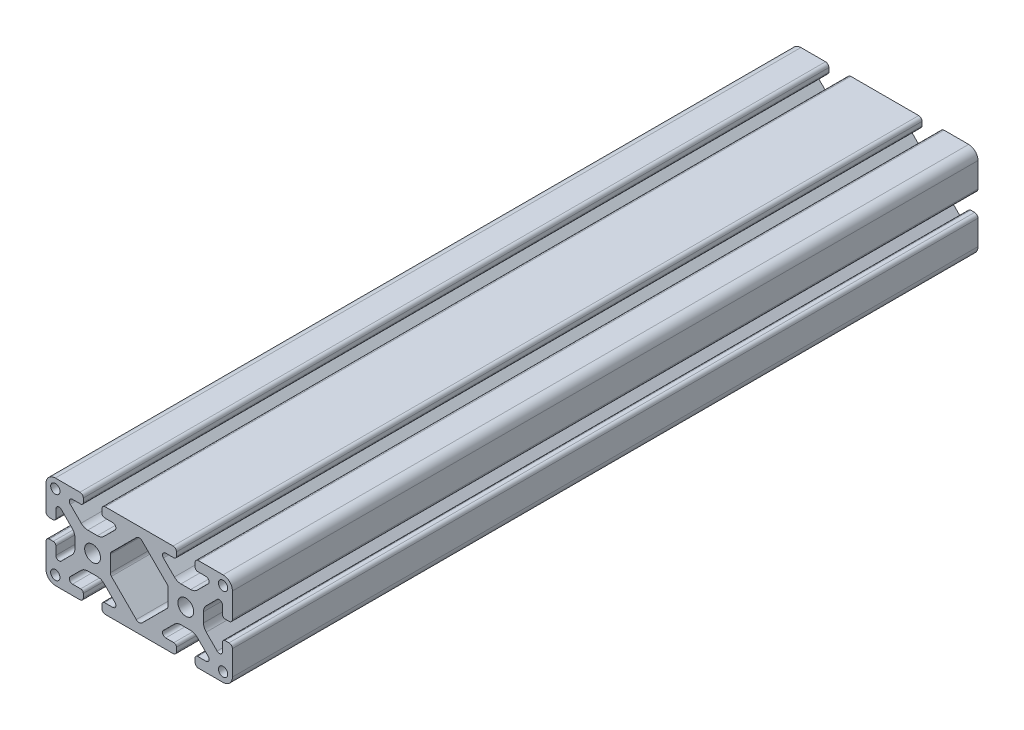
SolidWorks part; units mm, degrees
ref_plane "Front" through (0, 0, 0) normal (0, 0, 1) x (1, 0, 0)
ref_plane "Top" through (0, 0, 0) normal (0, 1, 0) x (1, 0, 0)
ref_plane "Right" through (0, 0, 0) normal (1, 0, 0) x (0, 0, -1)
sketch "Support-Front" plane through (0, 0, 0) normal (0, 0, 1) x (1, 0, 0)
  line L0 (50, 0) -> (-50, 0) construction
  line L1 (-50, -25) -> (50, -25)
  line L2 (-50, -25) -> (-50, 25)
  line L3 (-50, 25) -> (50, 25)
  line L4 (50, -25) -> (50, 25)
  line L5 (0, 25) -> (0, -25) construction
  dimension "Height-Profile" = 50
  dimension "Width-Profile" = 100
sketch "Support-Right-Length" plane through (0, 0, 0) normal (1, 0, 0) x (0, 0, -1)
  line L0 (0, -25) -> (0, 25) construction
  line L1 (-200, 25) -> (200, 25)
  line L2 (-200, 25) -> (-200, -25)
  line L3 (-200, -25) -> (200, -25)
  line L4 (200, 25) -> (200, -25)
  dimension "Length-Profile" = 400
sketch "Support-Profile" plane through (0, 0, 0) normal (0, 0, 1) x (1, 0, 0)
  line L12 (-14.9142, -5.6858) -> (-1.5556, -19.0444)
  line L13 (-15.5, 4.2716) -> (-15.5, -4.2716)
  line L14 (-1.5556, 19.0444) -> (-14.9142, 5.6858)
  line L15 (14.9142, 5.6858) -> (1.5556, 19.0444)
  line L16 (15.5, -4.2716) -> (15.5, 4.2716)
  line L17 (1.5556, -19.0444) -> (14.9142, -5.6858)
  line L104 (-30, -23.2) -> (-30, -21.1)
  line L105 (-31.4, -19.7) -> (-35.8, -19.7)
  line L106 (-36.9987, -16.7945) -> (-31.1255, -10.9545)
  line L107 (-27.6, -9.5) -> (-22.4, -9.5)
  line L108 (-18.8745, -10.9545) -> (-13.0013, -16.7945)
  line L109 (-14.2, -19.7) -> (-18.6, -19.7)
  line L110 (-20, -21.1) -> (-20, -23.2)
  line L111 (-18.2, -25) -> (18.2, -25)
  line L112 (20, -23.2) -> (20, -21.1)
  line L113 (18.6, -19.7) -> (14.2, -19.7)
  line L114 (13.0013, -16.7945) -> (18.8745, -10.9545)
  line L115 (22.4, -9.5) -> (27.6, -9.5)
  line L116 (31.1255, -10.9545) -> (36.9987, -16.7945)
  line L117 (35.8, -19.7) -> (31.4, -19.7)
  line L118 (30, -21.1) -> (30, -23.2)
  line L119 (31.8, -25) -> (45, -25)
  line L120 (50, -20) -> (50, -6.8)
  line L121 (48.2, -5) -> (46.1, -5)
  line L122 (44.7, -6.4) -> (44.7, -10.8)
  line L123 (41.7945, -11.9987) -> (35.9545, -6.1255)
  line L124 (34.5, -2.6) -> (34.5, 2.6)
  line L125 (35.9545, 6.1255) -> (41.7945, 11.9987)
  line L126 (44.7, 10.8) -> (44.7, 6.4)
  line L127 (46.1, 5) -> (48.2, 5)
  line L128 (50, 6.8) -> (50, 20)
  line L129 (45, 25) -> (31.8, 25)
  line L130 (30, 23.2) -> (30, 21.1)
  line L131 (31.4, 19.7) -> (35.8, 19.7)
  line L132 (36.9987, 16.7945) -> (31.1255, 10.9545)
  line L133 (27.6, 9.5) -> (22.4, 9.5)
  line L134 (18.8745, 10.9545) -> (13.0013, 16.7945)
  line L135 (14.2, 19.7) -> (18.6, 19.7)
  line L136 (20, 21.1) -> (20, 23.2)
  line L137 (18.2, 25) -> (-18.2, 25)
  line L138 (-20, 23.2) -> (-20, 21.1)
  line L139 (-18.6, 19.7) -> (-14.2, 19.7)
  line L140 (-13.0013, 16.7945) -> (-18.8745, 10.9545)
  line L141 (-22.4, 9.5) -> (-27.6, 9.5)
  line L142 (-31.1255, 10.9545) -> (-36.9987, 16.7945)
  line L143 (-35.8, 19.7) -> (-31.4, 19.7)
  line L144 (-30, 21.1) -> (-30, 23.2)
  line L145 (-31.8, 25) -> (-45, 25)
  line L146 (-50, 20) -> (-50, 6.8)
  line L147 (-48.2, 5) -> (-46.1, 5)
  line L148 (-44.7, 6.4) -> (-44.7, 10.8)
  line L149 (-41.7945, 11.9987) -> (-35.9545, 6.1255)
  line L150 (-34.5, 2.6) -> (-34.5, -2.6)
  line L151 (-35.9545, -6.1255) -> (-41.7945, -11.9987)
  line L152 (-44.7, -10.8) -> (-44.7, -6.4)
  line L153 (-46.1, -5) -> (-48.2, -5)
  line L154 (-50, -6.8) -> (-50, -20)
  line L155 (-45, -25) -> (-31.8, -25)
  circle A1 centre (-25, 0) radius 4.25
  circle A3 centre (-45, 20) radius 2.5
  circle A5 centre (-45, -20) radius 2.5
  arc A12 (-15.5, -4.2716) -> (-14.9142, -5.6858) centre (-13.5, -4.2716) ccw
  arc A13 (-14.9142, 5.6858) -> (-15.5, 4.2716) centre (-13.5, 4.2716) ccw
  arc A14 (1.5556, 19.0444) -> (-1.5556, 19.0444) centre (0, 17.4887) ccw
  arc A15 (15.5, 4.2716) -> (14.9142, 5.6858) centre (13.5, 4.2716) ccw
  arc A16 (14.9142, -5.6858) -> (15.5, -4.2716) centre (13.5, -4.2716) ccw
  arc A17 (-1.5556, -19.0444) -> (1.5556, -19.0444) centre (0, -17.4887) ccw
  circle A19 centre (25, 0) radius 4.25
  circle A21 centre (45, -20) radius 2.5
  circle A23 centre (45, 20) radius 2.5
  arc A104 (-30, -21.1) -> (-31.4, -19.7) centre (-31.4, -21.1) ccw
  arc A105 (-36.9987, -16.7945) -> (-35.8, -19.7) centre (-35.8, -18) ccw
  arc A106 (-27.6, -9.5) -> (-31.1255, -10.9545) centre (-27.6, -14.5) ccw
  arc A107 (-18.8745, -10.9545) -> (-22.4, -9.5) centre (-22.4, -14.5) ccw
  arc A108 (-14.2, -19.7) -> (-13.0013, -16.7945) centre (-14.2, -18) ccw
  arc A109 (-18.6, -19.7) -> (-20, -21.1) centre (-18.6, -21.1) ccw
  arc A110 (-20, -23.2) -> (-18.2, -25) centre (-18.2, -23.2) ccw
  arc A111 (18.2, -25) -> (20, -23.2) centre (18.2, -23.2) ccw
  arc A112 (20, -21.1) -> (18.6, -19.7) centre (18.6, -21.1) ccw
  arc A113 (13.0013, -16.7945) -> (14.2, -19.7) centre (14.2, -18) ccw
  arc A114 (22.4, -9.5) -> (18.8745, -10.9545) centre (22.4, -14.5) ccw
  arc A115 (31.1255, -10.9545) -> (27.6, -9.5) centre (27.6, -14.5) ccw
  arc A116 (35.8, -19.7) -> (36.9987, -16.7945) centre (35.8, -18) ccw
  arc A117 (31.4, -19.7) -> (30, -21.1) centre (31.4, -21.1) ccw
  arc A118 (30, -23.2) -> (31.8, -25) centre (31.8, -23.2) ccw
  arc A119 (45, -25) -> (50, -20) centre (45, -20) ccw
  arc A120 (50, -6.8) -> (48.2, -5) centre (48.2, -6.8) ccw
  arc A121 (46.1, -5) -> (44.7, -6.4) centre (46.1, -6.4) ccw
  arc A122 (41.7945, -11.9987) -> (44.7, -10.8) centre (43, -10.8) ccw
  arc A123 (34.5, -2.6) -> (35.9545, -6.1255) centre (39.5, -2.6) ccw
  arc A124 (35.9545, 6.1255) -> (34.5, 2.6) centre (39.5, 2.6) ccw
  arc A125 (44.7, 10.8) -> (41.7945, 11.9987) centre (43, 10.8) ccw
  arc A126 (44.7, 6.4) -> (46.1, 5) centre (46.1, 6.4) ccw
  arc A127 (48.2, 5) -> (50, 6.8) centre (48.2, 6.8) ccw
  arc A128 (50, 20) -> (45, 25) centre (45, 20) ccw
  arc A129 (31.8, 25) -> (30, 23.2) centre (31.8, 23.2) ccw
  arc A130 (30, 21.1) -> (31.4, 19.7) centre (31.4, 21.1) ccw
  arc A131 (36.9987, 16.7945) -> (35.8, 19.7) centre (35.8, 18) ccw
  arc A132 (27.6, 9.5) -> (31.1255, 10.9545) centre (27.6, 14.5) ccw
  arc A133 (18.8745, 10.9545) -> (22.4, 9.5) centre (22.4, 14.5) ccw
  arc A134 (14.2, 19.7) -> (13.0013, 16.7945) centre (14.2, 18) ccw
  arc A135 (18.6, 19.7) -> (20, 21.1) centre (18.6, 21.1) ccw
  arc A136 (20, 23.2) -> (18.2, 25) centre (18.2, 23.2) ccw
  arc A137 (-18.2, 25) -> (-20, 23.2) centre (-18.2, 23.2) ccw
  arc A138 (-20, 21.1) -> (-18.6, 19.7) centre (-18.6, 21.1) ccw
  arc A139 (-13.0013, 16.7945) -> (-14.2, 19.7) centre (-14.2, 18) ccw
  arc A140 (-22.4, 9.5) -> (-18.8745, 10.9545) centre (-22.4, 14.5) ccw
  arc A141 (-31.1255, 10.9545) -> (-27.6, 9.5) centre (-27.6, 14.5) ccw
  arc A142 (-35.8, 19.7) -> (-36.9987, 16.7945) centre (-35.8, 18) ccw
  arc A143 (-31.4, 19.7) -> (-30, 21.1) centre (-31.4, 21.1) ccw
  arc A144 (-30, 23.2) -> (-31.8, 25) centre (-31.8, 23.2) ccw
  arc A145 (-45, 25) -> (-50, 20) centre (-45, 20) ccw
  arc A146 (-50, 6.8) -> (-48.2, 5) centre (-48.2, 6.8) ccw
  arc A147 (-46.1, 5) -> (-44.7, 6.4) centre (-46.1, 6.4) ccw
  arc A148 (-41.7945, 11.9987) -> (-44.7, 10.8) centre (-43, 10.8) ccw
  arc A149 (-34.5, 2.6) -> (-35.9545, 6.1255) centre (-39.5, 2.6) ccw
  arc A150 (-35.9545, -6.1255) -> (-34.5, -2.6) centre (-39.5, -2.6) ccw
  arc A151 (-44.7, -10.8) -> (-41.7945, -11.9987) centre (-43, -10.8) ccw
  arc A152 (-44.7, -6.4) -> (-46.1, -5) centre (-46.1, -6.4) ccw
  arc A153 (-48.2, -5) -> (-50, -6.8) centre (-48.2, -6.8) ccw
  arc A154 (-50, -20) -> (-45, -25) centre (-45, -20) ccw
  arc A155 (-31.8, -25) -> (-30, -23.2) centre (-31.8, -23.2) ccw
ref_plane "Ref-Plane-1" through (0, 0, 200) normal (0, 0, 1) x (1, 0, 0)
ref_plane "Ref-Plane-2" through (0, 0, -200) normal (0, 0, 1) x (1, 0, 0)
sketch "Sketch4" plane through (0, 0, 200) normal (0, 0, 1) x (1, 0, 0)
  line L0 (-50, -25) -> (-50, 25) construction
  line L1 (-50, -25) -> (50, -25) construction
  line L2 (50, -25) -> (50, 25) construction
  line L3 (-50, 25) -> (50, 25) construction
  line L4 (-50, -25) -> (-50, 25)
  line L5 (-50, -25) -> (50, -25)
  line L6 (50, -25) -> (50, 25)
  line L7 (-50, 25) -> (50, 25)
extrude "Body" add sketch "Sketch4" against normal up to surface (400 mm away) up to plane "Ref-Plane-2"
sketch "Sketch6" plane through (0, 0, 0) normal (0, 0, 1) x (1, 0, 0)
  line L6 (14.9142, 5.6858) -> (1.5556, 19.0444)
  line L7 (-1.5556, 19.0444) -> (-14.9142, 5.6858)
  line L8 (-15.5, 4.2716) -> (-15.5, -4.2716)
  line L9 (-14.9142, -5.6858) -> (-1.5556, -19.0444)
  line L10 (1.5556, -19.0444) -> (14.9142, -5.6858)
  line L11 (15.5, -4.2716) -> (15.5, 4.2716)
  line L12 (14.9142, 5.6858) -> (1.5556, 19.0444)
  line L13 (-1.5556, 19.0444) -> (-14.9142, 5.6858)
  line L14 (-15.5, 4.2716) -> (-15.5, -4.2716)
  line L15 (-14.9142, -5.6858) -> (-1.5556, -19.0444)
  line L16 (1.5556, -19.0444) -> (14.9142, -5.6858)
  line L17 (15.5, -4.2716) -> (15.5, 4.2716)
  line L52 (-31.4, -19.7) -> (-35.8, -19.7)
  line L53 (-36.9987, -16.7945) -> (-31.1255, -10.9545)
  line L54 (-27.6, -9.5) -> (-22.4, -9.5)
  line L55 (-18.8745, -10.9545) -> (-13.0013, -16.7945)
  line L56 (-14.2, -19.7) -> (-18.6, -19.7)
  line L57 (-20, -21.1) -> (-20, -23.2)
  line L58 (-18.2, -25) -> (18.2, -25)
  line L59 (20, -23.2) -> (20, -21.1)
  line L60 (18.6, -19.7) -> (14.2, -19.7)
  line L61 (13.0013, -16.7945) -> (18.8745, -10.9545)
  line L62 (22.4, -9.5) -> (27.6, -9.5)
  line L63 (31.1255, -10.9545) -> (36.9987, -16.7945)
  line L64 (35.8, -19.7) -> (31.4, -19.7)
  line L65 (30, -21.1) -> (30, -23.2)
  line L66 (31.8, -25) -> (45, -25)
  line L67 (50, -20) -> (50, -6.8)
  line L68 (48.2, -5) -> (46.1, -5)
  line L69 (44.7, -6.4) -> (44.7, -10.8)
  line L70 (41.7945, -11.9987) -> (35.9545, -6.1255)
  line L71 (34.5, -2.6) -> (34.5, 2.6)
  line L72 (35.9545, 6.1255) -> (41.7945, 11.9987)
  line L73 (44.7, 10.8) -> (44.7, 6.4)
  line L74 (46.1, 5) -> (48.2, 5)
  line L75 (50, 6.8) -> (50, 20)
  line L76 (45, 25) -> (31.8, 25)
  line L77 (30, 23.2) -> (30, 21.1)
  line L78 (31.4, 19.7) -> (35.8, 19.7)
  line L79 (36.9987, 16.7945) -> (31.1255, 10.9545)
  line L80 (27.6, 9.5) -> (22.4, 9.5)
  line L81 (18.8745, 10.9545) -> (13.0013, 16.7945)
  line L82 (14.2, 19.7) -> (18.6, 19.7)
  line L83 (20, 21.1) -> (20, 23.2)
  line L84 (18.2, 25) -> (-18.2, 25)
  line L85 (-20, 23.2) -> (-20, 21.1)
  line L86 (-18.6, 19.7) -> (-14.2, 19.7)
  line L87 (-13.0013, 16.7945) -> (-18.8745, 10.9545)
  line L88 (-22.4, 9.5) -> (-27.6, 9.5)
  line L89 (-31.1255, 10.9545) -> (-36.9987, 16.7945)
  line L90 (-35.8, 19.7) -> (-31.4, 19.7)
  line L91 (-30, 21.1) -> (-30, 23.2)
  line L92 (-31.8, 25) -> (-45, 25)
  line L93 (-50, 20) -> (-50, 6.8)
  line L94 (-48.2, 5) -> (-46.1, 5)
  line L95 (-44.7, 6.4) -> (-44.7, 10.8)
  line L96 (-41.7945, 11.9987) -> (-35.9545, 6.1255)
  line L97 (-34.5, 2.6) -> (-34.5, -2.6)
  line L98 (-35.9545, -6.1255) -> (-41.7945, -11.9987)
  line L99 (-44.7, -10.8) -> (-44.7, -6.4)
  line L100 (-46.1, -5) -> (-48.2, -5)
  line L101 (-50, -6.8) -> (-50, -20)
  line L102 (-45, -25) -> (-31.8, -25)
  line L103 (-30, -23.2) -> (-30, -21.1)
  line L104 (-31.4, -19.7) -> (-35.8, -19.7)
  line L105 (-36.9987, -16.7945) -> (-31.1255, -10.9545)
  line L106 (-27.6, -9.5) -> (-22.4, -9.5)
  line L107 (-18.8745, -10.9545) -> (-13.0013, -16.7945)
  line L108 (-14.2, -19.7) -> (-18.6, -19.7)
  line L109 (-20, -21.1) -> (-20, -23.2)
  line L110 (-18.2, -25) -> (18.2, -25)
  line L111 (20, -23.2) -> (20, -21.1)
  line L112 (18.6, -19.7) -> (14.2, -19.7)
  line L113 (13.0013, -16.7945) -> (18.8745, -10.9545)
  line L114 (22.4, -9.5) -> (27.6, -9.5)
  line L115 (31.1255, -10.9545) -> (36.9987, -16.7945)
  line L116 (35.8, -19.7) -> (31.4, -19.7)
  line L117 (30, -21.1) -> (30, -23.2)
  line L118 (31.8, -25) -> (45, -25)
  line L119 (50, -20) -> (50, -6.8)
  line L120 (48.2, -5) -> (46.1, -5)
  line L121 (44.7, -6.4) -> (44.7, -10.8)
  line L122 (41.7945, -11.9987) -> (35.9545, -6.1255)
  line L123 (34.5, -2.6) -> (34.5, 2.6)
  line L124 (35.9545, 6.1255) -> (41.7945, 11.9987)
  line L125 (44.7, 10.8) -> (44.7, 6.4)
  line L126 (46.1, 5) -> (48.2, 5)
  line L127 (50, 6.8) -> (50, 20)
  line L128 (45, 25) -> (31.8, 25)
  line L129 (30, 23.2) -> (30, 21.1)
  line L130 (31.4, 19.7) -> (35.8, 19.7)
  line L131 (36.9987, 16.7945) -> (31.1255, 10.9545)
  line L132 (27.6, 9.5) -> (22.4, 9.5)
  line L133 (18.8745, 10.9545) -> (13.0013, 16.7945)
  line L134 (14.2, 19.7) -> (18.6, 19.7)
  line L135 (20, 21.1) -> (20, 23.2)
  line L136 (18.2, 25) -> (-18.2, 25)
  line L137 (-20, 23.2) -> (-20, 21.1)
  line L138 (-18.6, 19.7) -> (-14.2, 19.7)
  line L139 (-13.0013, 16.7945) -> (-18.8745, 10.9545)
  line L140 (-22.4, 9.5) -> (-27.6, 9.5)
  line L141 (-31.1255, 10.9545) -> (-36.9987, 16.7945)
  line L142 (-35.8, 19.7) -> (-31.4, 19.7)
  line L143 (-30, 21.1) -> (-30, 23.2)
  line L144 (-31.8, 25) -> (-45, 25)
  line L145 (-50, 20) -> (-50, 6.8)
  line L146 (-48.2, 5) -> (-46.1, 5)
  line L147 (-44.7, 6.4) -> (-44.7, 10.8)
  line L148 (-41.7945, 11.9987) -> (-35.9545, 6.1255)
  line L149 (-34.5, 2.6) -> (-34.5, -2.6)
  line L150 (-35.9545, -6.1255) -> (-41.7945, -11.9987)
  line L151 (-44.7, -10.8) -> (-44.7, -6.4)
  line L152 (-46.1, -5) -> (-48.2, -5)
  line L153 (-50, -6.8) -> (-50, -20)
  line L154 (-45, -25) -> (-31.8, -25)
  line L155 (-30, -23.2) -> (-30, -21.1)
  circle A0 centre (25, 0) radius 4.25 construction
  circle A1 centre (45, -20) radius 2.5 construction
  circle A2 centre (45, 20) radius 2.5 construction
  circle A3 centre (-45, -20) radius 2.5 construction
  circle A4 centre (-45, 20) radius 2.5 construction
  circle A5 centre (-25, 0) radius 4.25 construction
  circle A6 centre (25, 0) radius 4.25
  circle A7 centre (45, -20) radius 2.5
  circle A8 centre (45, 20) radius 2.5
  circle A9 centre (-45, -20) radius 2.5
  circle A10 centre (-45, 20) radius 2.5
  circle A11 centre (-25, 0) radius 4.25
  arc A18 (1.5556, 19.0444) -> (-1.5556, 19.0444) centre (0, 17.4887) ccw
  arc A19 (-14.9142, 5.6858) -> (-15.5, 4.2716) centre (-13.5, 4.2716) ccw
  arc A20 (-15.5, -4.2716) -> (-14.9142, -5.6858) centre (-13.5, -4.2716) ccw
  arc A21 (-1.5556, -19.0444) -> (1.5556, -19.0444) centre (0, -17.4887) ccw
  arc A22 (14.9142, -5.6858) -> (15.5, -4.2716) centre (13.5, -4.2716) ccw
  arc A23 (15.5, 4.2716) -> (14.9142, 5.6858) centre (13.5, 4.2716) ccw
  arc A24 (1.5556, 19.0444) -> (-1.5556, 19.0444) centre (0, 17.4887) ccw
  arc A25 (-14.9142, 5.6858) -> (-15.5, 4.2716) centre (-13.5, 4.2716) ccw
  arc A26 (-15.5, -4.2716) -> (-14.9142, -5.6858) centre (-13.5, -4.2716) ccw
  arc A27 (-1.5556, -19.0444) -> (1.5556, -19.0444) centre (0, -17.4887) ccw
  arc A28 (14.9142, -5.6858) -> (15.5, -4.2716) centre (13.5, -4.2716) ccw
  arc A29 (15.5, 4.2716) -> (14.9142, 5.6858) centre (13.5, 4.2716) ccw
  arc A52 (-36.9987, -16.7945) -> (-35.8, -19.7) centre (-35.8, -18) ccw
  arc A53 (-27.6, -9.5) -> (-31.1255, -10.9545) centre (-27.6, -14.5) ccw
  arc A54 (-18.8745, -10.9545) -> (-22.4, -9.5) centre (-22.4, -14.5) ccw
  arc A55 (-14.2, -19.7) -> (-13.0013, -16.7945) centre (-14.2, -18) ccw
  arc A56 (-18.6, -19.7) -> (-20, -21.1) centre (-18.6, -21.1) ccw
  arc A57 (-20, -23.2) -> (-18.2, -25) centre (-18.2, -23.2) ccw
  arc A59 (18.2, -25) -> (20, -23.2) centre (18.2, -23.2) ccw
  arc A60 (20, -21.1) -> (18.6, -19.7) centre (18.6, -21.1) ccw
  arc A61 (13.0013, -16.7945) -> (14.2, -19.7) centre (14.2, -18) ccw
  arc A62 (22.4, -9.5) -> (18.8745, -10.9545) centre (22.4, -14.5) ccw
  arc A63 (31.1255, -10.9545) -> (27.6, -9.5) centre (27.6, -14.5) ccw
  arc A64 (35.8, -19.7) -> (36.9987, -16.7945) centre (35.8, -18) ccw
  arc A65 (31.4, -19.7) -> (30, -21.1) centre (31.4, -21.1) ccw
  arc A66 (30, -23.2) -> (31.8, -25) centre (31.8, -23.2) ccw
  arc A67 (45, -25) -> (50, -20) centre (45, -20) ccw
  arc A68 (50, -6.8) -> (48.2, -5) centre (48.2, -6.8) ccw
  arc A69 (46.1, -5) -> (44.7, -6.4) centre (46.1, -6.4) ccw
  arc A70 (41.7945, -11.9987) -> (44.7, -10.8) centre (43, -10.8) ccw
  arc A71 (34.5, -2.6) -> (35.9545, -6.1255) centre (39.5, -2.6) ccw
  arc A72 (35.9545, 6.1255) -> (34.5, 2.6) centre (39.5, 2.6) ccw
  arc A73 (44.7, 10.8) -> (41.7945, 11.9987) centre (43, 10.8) ccw
  arc A74 (44.7, 6.4) -> (46.1, 5) centre (46.1, 6.4) ccw
  arc A75 (48.2, 5) -> (50, 6.8) centre (48.2, 6.8) ccw
  arc A76 (50, 20) -> (45, 25) centre (45, 20) ccw
  arc A77 (31.8, 25) -> (30, 23.2) centre (31.8, 23.2) ccw
  arc A78 (30, 21.1) -> (31.4, 19.7) centre (31.4, 21.1) ccw
  arc A79 (36.9987, 16.7945) -> (35.8, 19.7) centre (35.8, 18) ccw
  arc A80 (27.6, 9.5) -> (31.1255, 10.9545) centre (27.6, 14.5) ccw
  arc A81 (18.8745, 10.9545) -> (22.4, 9.5) centre (22.4, 14.5) ccw
  arc A82 (14.2, 19.7) -> (13.0013, 16.7945) centre (14.2, 18) ccw
  arc A83 (18.6, 19.7) -> (20, 21.1) centre (18.6, 21.1) ccw
  arc A84 (20, 23.2) -> (18.2, 25) centre (18.2, 23.2) ccw
  arc A85 (-18.2, 25) -> (-20, 23.2) centre (-18.2, 23.2) ccw
  arc A86 (-20, 21.1) -> (-18.6, 19.7) centre (-18.6, 21.1) ccw
  arc A87 (-13.0013, 16.7945) -> (-14.2, 19.7) centre (-14.2, 18) ccw
  arc A88 (-22.4, 9.5) -> (-18.8745, 10.9545) centre (-22.4, 14.5) ccw
  arc A89 (-31.1255, 10.9545) -> (-27.6, 9.5) centre (-27.6, 14.5) ccw
  arc A90 (-35.8, 19.7) -> (-36.9987, 16.7945) centre (-35.8, 18) ccw
  arc A91 (-31.4, 19.7) -> (-30, 21.1) centre (-31.4, 21.1) ccw
  arc A92 (-30, 23.2) -> (-31.8, 25) centre (-31.8, 23.2) ccw
  arc A93 (-45, 25) -> (-50, 20) centre (-45, 20) ccw
  arc A94 (-50, 6.8) -> (-48.2, 5) centre (-48.2, 6.8) ccw
  arc A95 (-46.1, 5) -> (-44.7, 6.4) centre (-46.1, 6.4) ccw
  arc A96 (-41.7945, 11.9987) -> (-44.7, 10.8) centre (-43, 10.8) ccw
  arc A97 (-34.5, 2.6) -> (-35.9545, 6.1255) centre (-39.5, 2.6) ccw
  arc A98 (-35.9545, -6.1255) -> (-34.5, -2.6) centre (-39.5, -2.6) ccw
  arc A99 (-44.7, -10.8) -> (-41.7945, -11.9987) centre (-43, -10.8) ccw
  arc A100 (-44.7, -6.4) -> (-46.1, -5) centre (-46.1, -6.4) ccw
  arc A101 (-48.2, -5) -> (-50, -6.8) centre (-48.2, -6.8) ccw
  arc A102 (-50, -20) -> (-45, -25) centre (-45, -20) ccw
  arc A103 (-31.8, -25) -> (-30, -23.2) centre (-31.8, -23.2) ccw
  arc A104 (-30, -21.1) -> (-31.4, -19.7) centre (-31.4, -21.1) ccw
  arc A105 (-36.9987, -16.7945) -> (-35.8, -19.7) centre (-35.8, -18) ccw
  arc A106 (-27.6, -9.5) -> (-31.1255, -10.9545) centre (-27.6, -14.5) ccw
  arc A107 (-18.8745, -10.9545) -> (-22.4, -9.5) centre (-22.4, -14.5) ccw
  arc A108 (-14.2, -19.7) -> (-13.0013, -16.7945) centre (-14.2, -18) ccw
  arc A109 (-18.6, -19.7) -> (-20, -21.1) centre (-18.6, -21.1) ccw
  arc A110 (-20, -23.2) -> (-18.2, -25) centre (-18.2, -23.2) ccw
  arc A111 (18.2, -25) -> (20, -23.2) centre (18.2, -23.2) ccw
  arc A112 (20, -21.1) -> (18.6, -19.7) centre (18.6, -21.1) ccw
  arc A113 (13.0013, -16.7945) -> (14.2, -19.7) centre (14.2, -18) ccw
  arc A114 (22.4, -9.5) -> (18.8745, -10.9545) centre (22.4, -14.5) ccw
  arc A115 (31.1255, -10.9545) -> (27.6, -9.5) centre (27.6, -14.5) ccw
  arc A116 (35.8, -19.7) -> (36.9987, -16.7945) centre (35.8, -18) ccw
  arc A117 (31.4, -19.7) -> (30, -21.1) centre (31.4, -21.1) ccw
  arc A118 (30, -23.2) -> (31.8, -25) centre (31.8, -23.2) ccw
  arc A119 (45, -25) -> (50, -20) centre (45, -20) ccw
  arc A120 (50, -6.8) -> (48.2, -5) centre (48.2, -6.8) ccw
  arc A121 (46.1, -5) -> (44.7, -6.4) centre (46.1, -6.4) ccw
  arc A122 (41.7945, -11.9987) -> (44.7, -10.8) centre (43, -10.8) ccw
  arc A123 (34.5, -2.6) -> (35.9545, -6.1255) centre (39.5, -2.6) ccw
  arc A124 (35.9545, 6.1255) -> (34.5, 2.6) centre (39.5, 2.6) ccw
  arc A125 (44.7, 10.8) -> (41.7945, 11.9987) centre (43, 10.8) ccw
  arc A126 (44.7, 6.4) -> (46.1, 5) centre (46.1, 6.4) ccw
  arc A127 (48.2, 5) -> (50, 6.8) centre (48.2, 6.8) ccw
  arc A128 (50, 20) -> (45, 25) centre (45, 20) ccw
  arc A129 (31.8, 25) -> (30, 23.2) centre (31.8, 23.2) ccw
  arc A130 (30, 21.1) -> (31.4, 19.7) centre (31.4, 21.1) ccw
  arc A131 (36.9987, 16.7945) -> (35.8, 19.7) centre (35.8, 18) ccw
  arc A132 (27.6, 9.5) -> (31.1255, 10.9545) centre (27.6, 14.5) ccw
  arc A133 (18.8745, 10.9545) -> (22.4, 9.5) centre (22.4, 14.5) ccw
  arc A134 (14.2, 19.7) -> (13.0013, 16.7945) centre (14.2, 18) ccw
  arc A135 (18.6, 19.7) -> (20, 21.1) centre (18.6, 21.1) ccw
  arc A136 (20, 23.2) -> (18.2, 25) centre (18.2, 23.2) ccw
  arc A137 (-18.2, 25) -> (-20, 23.2) centre (-18.2, 23.2) ccw
  arc A138 (-20, 21.1) -> (-18.6, 19.7) centre (-18.6, 21.1) ccw
  arc A139 (-13.0013, 16.7945) -> (-14.2, 19.7) centre (-14.2, 18) ccw
  arc A140 (-22.4, 9.5) -> (-18.8745, 10.9545) centre (-22.4, 14.5) ccw
  arc A141 (-31.1255, 10.9545) -> (-27.6, 9.5) centre (-27.6, 14.5) ccw
  arc A142 (-35.8, 19.7) -> (-36.9987, 16.7945) centre (-35.8, 18) ccw
  arc A143 (-31.4, 19.7) -> (-30, 21.1) centre (-31.4, 21.1) ccw
  arc A144 (-30, 23.2) -> (-31.8, 25) centre (-31.8, 23.2) ccw
  arc A145 (-45, 25) -> (-50, 20) centre (-45, 20) ccw
  arc A146 (-50, 6.8) -> (-48.2, 5) centre (-48.2, 6.8) ccw
  arc A147 (-46.1, 5) -> (-44.7, 6.4) centre (-46.1, 6.4) ccw
  arc A148 (-41.7945, 11.9987) -> (-44.7, 10.8) centre (-43, 10.8) ccw
  arc A149 (-34.5, 2.6) -> (-35.9545, 6.1255) centre (-39.5, 2.6) ccw
  arc A150 (-35.9545, -6.1255) -> (-34.5, -2.6) centre (-39.5, -2.6) ccw
  arc A151 (-44.7, -10.8) -> (-41.7945, -11.9987) centre (-43, -10.8) ccw
  arc A152 (-44.7, -6.4) -> (-46.1, -5) centre (-46.1, -6.4) ccw
  arc A153 (-48.2, -5) -> (-50, -6.8) centre (-48.2, -6.8) ccw
  arc A154 (-50, -20) -> (-45, -25) centre (-45, -20) ccw
  arc A155 (-31.8, -25) -> (-30, -23.2) centre (-31.8, -23.2) ccw
  arc A156 (-30, -21.1) -> (-31.4, -19.7) centre (-31.4, -21.1) ccw
  dimension "D1" = 0
  dimension "D2" = 0
extrude "Cut-Profile" cut sketch "Sketch6" against normal through all and the other way through all flip side to cut
